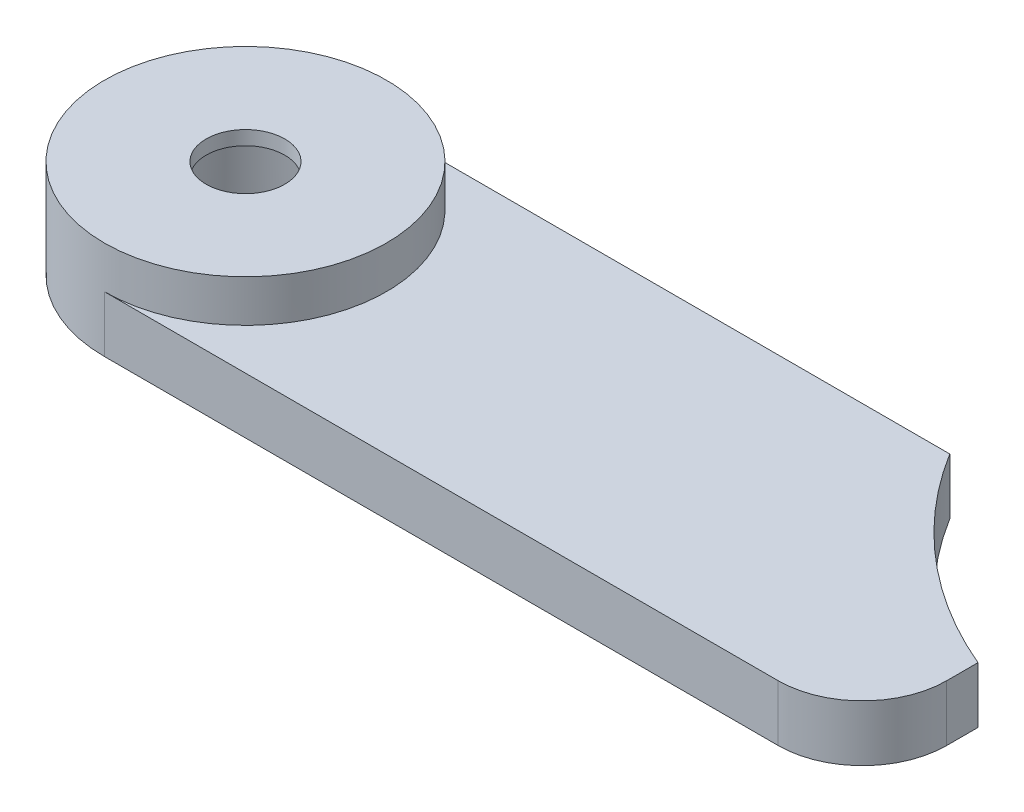
SolidWorks part; units mm, degrees
ref_plane "Front Plane" through (0, 0, 0) normal (0, 0, 1) x (1, 0, 0)
ref_plane "Top Plane" through (0, 0, 0) normal (0, 1, 0) x (1, 0, 0)
ref_plane "Right Plane" through (0, 0, 0) normal (1, 0, 0) x (0, 0, -1)
sketch "Sketch1" plane through (0, 0, 0) normal (0, 1, 0) x (1, 0, 0)
  circle A0 centre (0, 0) radius 2.025
  circle A1 centre (0, 0) radius 5.025
  dimension "D1" = 4.05
  dimension "D2" = 3
extrude "Boss-Extrude1" add sketch "Sketch1" along normal blind 3
sketch "Sketch2" plane through (0, 0, 0) normal (0, -1, 0) x (1, 0, 0)
  line L1 (0, 5.025) -> (27, 5.025)
  line L2 (0, 5.025) -> (0, -5.025)
  line L3 (0, -5.025) -> (27, -5.025)
  line L4 (27, 5.025) -> (27, -5.025)
  circle A0 centre (0, 0) radius 5.025 construction
  circle A1 centre (0, 0) radius 5.025 construction
  dimension "D1" = 27
extrude "Boss-Extrude2" add sketch "Sketch2" against normal blind 2
sketch "Sketch3" plane through (0, 2, 0) normal (0, 1, 0) x (1, 0, 0)
  circle A0 centre (32.8162, 12.9174) radius 15
  dimension "D1" = 30
extrude "Cut-Extrude1" cut sketch "Sketch3" against normal blind 2
fillet "Fillet1" radius 3 1 edges at (27, 1, 5.025)
sketch "Sketch4" plane through (0, 3, 0) normal (0, 1, 0) x (1, 0, 0)
  circle A0 centre (0, 0) radius 2.5
  dimension "D1" = 5
extrude "Cut-Extrude2" cut sketch "Sketch4" against normal blind 10 draft 5 draft outward yes
sketch "Sketch5" plane through (0, 3, 0) normal (0, 1, 0) x (1, 0, 0)
  circle A0 centre (0, 0) radius 5.025
extrude "Boss-Extrude3" add sketch "Sketch5" along normal blind 0.5
sketch "Sketch6" plane through (0, 3, 0) normal (0, -1, 0) x (1, 0, 0)
  circle A0 centre (0, 0) radius 1.4
  dimension "D1" = 2.8
extrude "Cut-Extrude3" cut sketch "Sketch6" against normal blind 0.5
